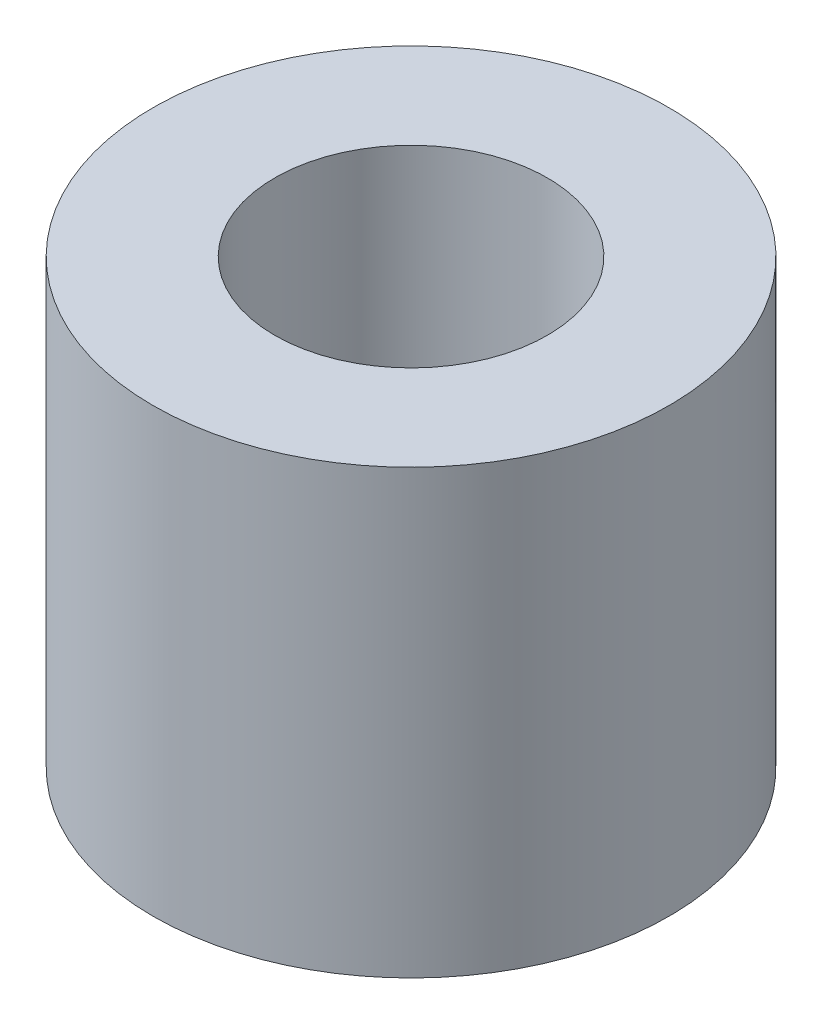
SolidWorks part; units mm, degrees
ref_plane "前视基准面" through (0, 0, 0) normal (0, 0, 1) x (1, 0, 0)
ref_plane "上视基准面" through (0, 0, 0) normal (0, 1, 0) x (1, 0, 0)
ref_plane "右视基准面" through (0, 0, 0) normal (1, 0, 0) x (0, 0, -1)
sketch "草图1" plane through (0, 0, 0) normal (0, 1, 0) x (1, 0, 0)
  circle A0 centre (0, 0) radius 1.85
  circle A1 centre (0, 0) radius 3.5
  dimension "D1" = 3.7
  dimension "D2" = 7
extrude "凸台-拉伸1" add sketch "草图1" along normal blind 6
